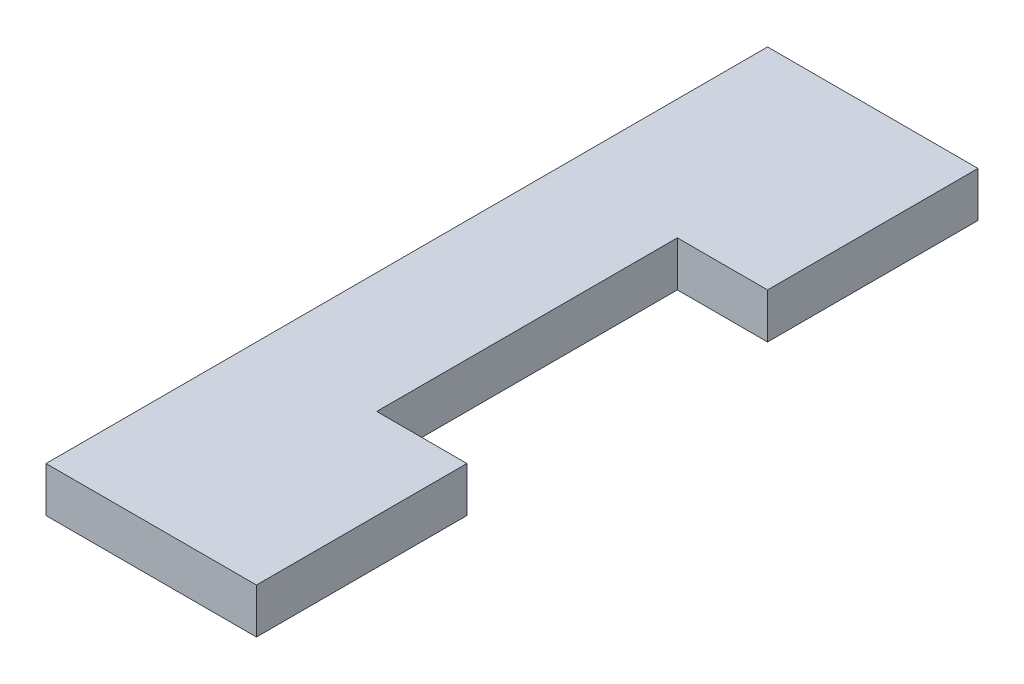
SolidWorks part; units mm, degrees
material "Pine"
ref_plane "Front Plane" through (0, 0, 0) normal (0, 0, 1) x (1, 0, 0)
ref_plane "Top Plane" through (0, 0, 0) normal (0, 1, 0) x (1, 0, 0)
ref_plane "Right Plane" through (0, 0, 0) normal (1, 0, 0) x (0, 0, -1)
sketch "Sketch1" plane through (0, 0, 0) normal (0, 1, 0) x (1, 0, 0)
  line L0 (0, 0) -> (0, 304.8)
  line L1 (0, 304.8) -> (88.9, 304.8)
  line L2 (88.9, 304.8) -> (88.9, 215.9)
  line L3 (88.9, 215.9) -> (50.8, 215.9)
  line L4 (50.8, 215.9) -> (50.8, 88.9)
  line L5 (50.8, 88.9) -> (88.9, 88.9)
  line L6 (88.9, 88.9) -> (88.9, 0)
  line L7 (88.9, 0) -> (0, 0)
  dimension "D1" = 304.8
  dimension "D2" = 88.9
  dimension "D3" = 88.9
  dimension "D4" = 88.9
  dimension "D5" = 38.1
  dimension "D6" = 127
  dimension "D7" = 88.9
extrude "Boss-Extrude1" add sketch "Sketch1" along normal blind 19.05
